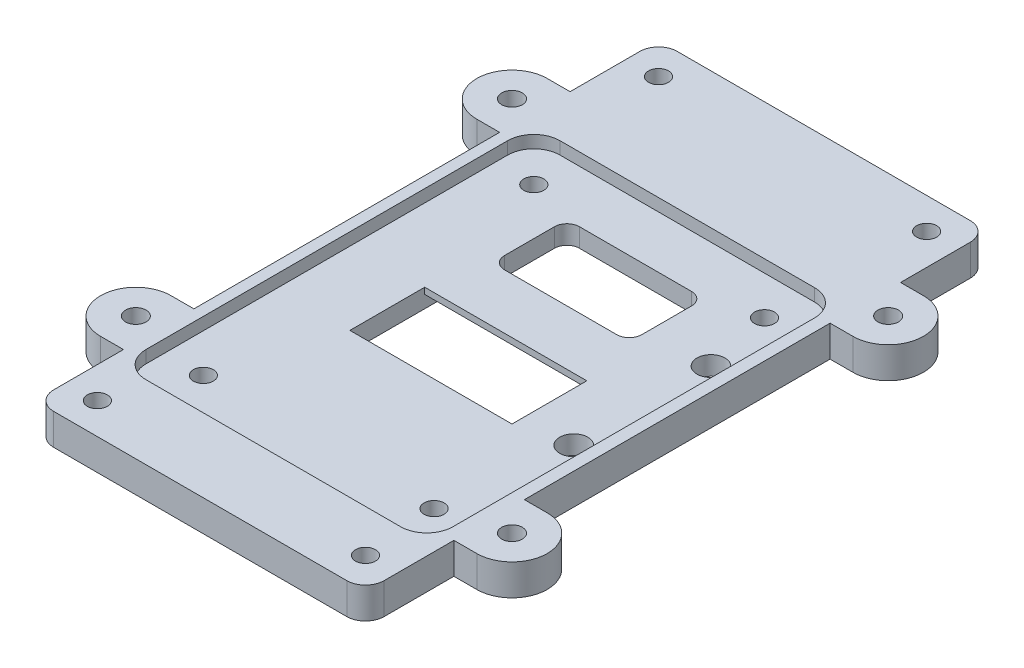
SolidWorks part; units mm, degrees
ref_plane "Front Plane" through (0, 0, 0) normal (0, 0, 1) x (1, 0, 0)
ref_plane "Top Plane" through (0, 0, 0) normal (0, 1, 0) x (1, 0, 0)
ref_plane "Right Plane" through (0, 0, 0) normal (1, 0, 0) x (0, 0, -1)
sketch "Sketch1" plane through (0, 0, 0) normal (0, 1, 0) x (1, 0, 0)
  line L1 (23.5, -32) -> (-23.5, -32)
  line L2 (23.5, -32) -> (23.5, 32)
  line L3 (23.5, 32) -> (-23.5, 32)
  line L4 (-23.5, -32) -> (-23.5, 32)
  line L5 (23.5, -32) -> (-23.5, 32) construction
  line L6 (23.5, 32) -> (-23.5, -32) construction
  point P0 (0, 0)
  dimension "D1" = 47
  dimension "D2" = 64
extrude "Boss-Extrude1" add sketch "Sketch1" along normal blind 5 contours L2 L1 L4 L3
sketch "Sketch2" plane through (0, 5, 0) normal (0, 1, 0) x (1, 0, 0)
  line L0 (-23.5, 0) -> (23.5, 0) construction
  line L1 (-23.5, -32) -> (-23.5, 32) construction
  line L2 (23.5, -32) -> (23.5, 32) construction
  line L3 (0, 0) -> (0, -8) construction
  line L4 (0, -8) -> (13, -8) construction
  line L5 (13, -8) -> (13, 4)
  line L6 (13, 4) -> (-13, 4)
  line L7 (0, 0) -> (0, 18.81) construction
  line L8 (13, -8) -> (-13, -8)
  line L9 (13, -8) -> (13, 4)
  line L10 (13, 4) -> (-13, 4)
  line L11 (-13, -8) -> (-13, 4)
  line L13 (-11, 12.81) -> (11, 12.81)
  line L14 (-11, 12.81) -> (-11, 24.81)
  line L15 (-11, 24.81) -> (11, 24.81)
  line L16 (11, 12.81) -> (11, 24.81)
  line L17 (-11, 12.81) -> (11, 24.81) construction
  line L18 (-11, 24.81) -> (11, 12.81) construction
  dimension "D1" = 8
  dimension "D2" = 13
  dimension "D3" = 12
  dimension "D4" = 26
  dimension "D5" = 18.81
  dimension "D6" = 22
  dimension "D7" = 12
extrude "Cut-Extrude1" cut sketch "Sketch2" against normal blind 5 contours L13 L16 L15 L14 | L11 L8 L5 L6
sketch "Sketch3" plane through (0, 5, 0) normal (0, 1, 0) x (1, 0, 0)
  line L0 (23.5, 32) -> (-23.5, 32) construction
  line L1 (-23.5, -32) -> (-23.5, 32) construction
  line L2 (0, 0) -> (0, 8.2932) construction
  line L3 (23.5, -32) -> (-23.5, -32) construction
  circle A0 centre (-18.5, 27) radius 1.6
  circle A1 centre (18.5, 27) radius 1.6
  circle A2 centre (-18.5, -26) radius 1.6
  circle A3 centre (18.5, -26) radius 1.6
  dimension "D1" = 3.2
  dimension "D4" = 3.2
  dimension "D2" = 5
  dimension "D3" = 5
  dimension "D5" = 5
  dimension "D6" = 6
extrude "Cut-Extrude2" cut sketch "Sketch3" against normal blind 63
fillet "Fillet1" radius 2 4 edges at (11, 2.5, -12.81) (-11, 2.5, -12.81) (11, 2.5, -24.81) (-11, 2.5, -24.81)
fillet "Fillet2" radius 3 4 edges at (23.5, 2.5, -32) (-23.5, 2.5, -32) (23.5, 2.5, 32) (-23.5, 2.5, 32)
sketch "Sketch5" plane through (0, 5, 0) normal (0, 1, 0) x (1, 0, 0)
  line L0 (-23.5, -29) -> (-23.5, 29) construction
  line L1 (-23.5, -25.165) -> (-23.5, 29)
  line L2 (-23.5, 29) -> (-23.5, 5)
  line L3 (-23.5, 5) -> (23.5, 5) construction
  line L4 (23.5, -29) -> (23.5, 29) construction
  line L5 (-30.165, 40.815) -> (-26.5, 40.815)
  line L6 (-30.165, -25.165) -> (-28.515, -25.165)
  line L7 (-30.165, -25.165) -> (-30.165, 35.165)
  line L8 (-30.165, 35.165) -> (15.9874, 35.165)
  line L10 (-30.165, -25.165) -> (-28.9983, -23.9983) construction
  line L11 (-30.165, 35.165) -> (-28.9983, 33.9983) construction
  line L12 (-26.5, -45) -> (26.5, -45)
  line L13 (-26.5, -45) -> (-26.5, -30.815)
  line L14 (-26.5, 55) -> (26.5, 55)
  line L15 (26.5, -45) -> (26.5, -30.815)
  line L16 (-26.5, -45) -> (26.5, 55) construction
  line L17 (-26.5, 55) -> (26.5, -45) construction
  line L18 (-30.165, 29.515) -> (-26.5, 29.515)
  line L19 (-26.5, 40.815) -> (-26.5, 55)
  line L20 (-23.5, 28.5) -> (0, 5) construction
  line L21 (30.165, 40.815) -> (26.5, 40.815)
  line L22 (30.165, 29.515) -> (26.5, 29.515)
  line L23 (28.515, 35.165) -> (30.165, 35.165)
  line L24 (26.5, 40.815) -> (26.5, 55)
  line L25 (26.1698, 31.1698) -> (30.165, 35.165) construction
  line L26 (30.165, 33.515) -> (30.165, 35.165)
  line L27 (-30.165, -19.515) -> (-26.5, -19.515)
  line L28 (-30.165, -30.815) -> (-26.5, -30.815)
  line L29 (-26.5, -19.515) -> (-26.5, 29.515)
  line L30 (-23.5, -18.5) -> (0, 5) construction
  line L31 (-23.5, -25.165) -> (24.515, -25.165)
  line L34 (26.5, -9.515) -> (26.5, 29.515)
  line L35 (28.515, -25.165) -> (30.165, -25.165)
  line L36 (30.165, 35.165) -> (30.165, -25.165)
  line L37 (26.5, -9.515) -> (26.5, -19.515)
  line L38 (0, 0) -> (0, -5.5658) construction
  line L39 (30.165, -19.515) -> (26.5, -19.515)
  line L40 (30.165, -30.815) -> (26.5, -30.815)
  circle A0 centre (-30.165, 35.165) radius 1.65
  circle A1 centre (30.165, 35.165) radius 1.65
  circle A2 centre (30.165, -25.165) radius 1.65
  circle A3 centre (-30.165, -25.165) radius 1.65
  arc A4 (30.165, -19.515) -> (30.165, -30.815) centre (30.165, -25.165) cw
  arc A5 (-30.165, 40.815) -> (-30.165, 29.515) centre (-30.165, 35.165) ccw
  arc A6 (-30.165, -19.515) -> (-30.165, -30.815) centre (-30.165, -25.165) ccw
  arc A8 (30.165, 29.515) -> (30.165, 40.815) centre (30.165, 35.165) ccw
  circle A9 centre (-30.165, 35.165) radius 5.65 construction
  circle A10 centre (30.165, 35.165) radius 5.65 construction
  circle A11 centre (-30.165, -25.165) radius 5.65 construction
  point P2 (0, 5)
  point P15 (0, 5)
  dimension "D4" = 3.3
  dimension "D5" = 3.3
  dimension "D6" = 3.3
  dimension "D7" = 3.3
  dimension "D10" = 4
  dimension "D1" = 24
  dimension "D2" = 60.33
  dimension "D3" = 60.33
  dimension "D8" = 100
  dimension "D9" = 53
extrude "Boss-Extrude3" add sketch "Sketch5" against normal up to surface (5 mm away)
sketch "Sketch6" plane through (0, 5, 0) normal (0, 1, 0) x (1, 0, 0)
  line L0 (23.3314, 0) -> (-23.3314, 0)
  line L1 (0, 0) -> (0, -32) construction
  line L2 (0, 0) -> (0, 32) construction
  line L4 (-23.5, 32) -> (23.5, 32) construction
  line L13 (-20.5, 32) -> (20.3314, 32)
  line L14 (-23.5, 29) -> (-23.5, -29)
  line L15 (-20.5, -32) -> (20.3314, -32)
  line L16 (23.3314, 29) -> (23.3314, -29)
  line L17 (-24.7, 29) -> (-24.7, -29)
  line L18 (-20.5, -33.2) -> (20.3314, -33.2)
  line L19 (24.5314, 29) -> (24.5314, -29)
  line L20 (-20.5, 33.2) -> (20.3314, 33.2)
  arc A0 (20.3314, -32) -> (23.3314, -29) centre (20.3314, -29) ccw
  arc A1 (-20.5, -32) -> (-23.5, -29) centre (-20.5, -29) cw
  arc A2 (23.3314, 29) -> (20.3314, 32) centre (20.3314, 29) ccw
  arc A3 (-20.5, 32) -> (-23.5, 29) centre (-20.5, 29) ccw
  arc A4 (-20.5, -33.2) -> (-24.7, -29) centre (-20.5, -29) cw
  arc A5 (20.3314, -33.2) -> (24.5314, -29) centre (20.3314, -29) ccw
  arc A6 (24.5314, 29) -> (20.3314, 33.2) centre (20.3314, 29) ccw
  arc A7 (-20.5, 33.2) -> (-24.7, 29) centre (-20.5, 29) ccw
  point P4 (0, 0)
  point P10 (0, 32)
  point P11 (0, 32)
  dimension "D1" = 3
  dimension "D3" = 47
extrude "Cut-Extrude5" cut sketch "Sketch6" against normal blind 2
sketch "Sketch7" plane through (0, 0, 0) normal (0, -1, 0) x (1, 0, 0)
  line L0 (-26.5, 45) -> (26.5, 45) construction
  line L1 (-26.5, 45) -> (-26.5, 30.815) construction
  line L2 (0, 0) -> (0, 8) construction
  line L3 (13, 8) -> (-13, 8) construction
  line L4 (-26.5, -40.815) -> (-26.5, -55) construction
  line L5 (-26.5, -55) -> (26.5, -55) construction
  circle A0 centre (-21.5, 40) radius 1.6
  circle A1 centre (21.5, 40) radius 1.6
  circle A2 centre (-21.5, -50) radius 1.6
  circle A3 centre (21.5, -50) radius 1.6
  dimension "D5" = 3.2
  dimension "D6" = 3.2
  dimension "D1" = 5
  dimension "D2" = 5
  dimension "D3" = 5
  dimension "D4" = 5
extrude "Cut-Extrude7" cut sketch "Sketch7" against normal through all
chamfer "Chamfer4" distance 2 angle 45 2 edges at (0, 0, 8) (0, 0, -4)
fillet "Fillet3" radius 3 4 edges at (26.5, 2.5, 45) (-26.5, 2.5, 45) (-26.5, 2.5, -55) (26.5, 2.5, -55)
sketch "Sketch8" plane through (0, 0, 0) normal (0, -1, 0) x (1, 0, 0)
  line L0 (-30.165, -5) -> (30.165, -5) construction
  line L1 (-30.165, -35.165) -> (30.165, -35.165)
  line L2 (-30.165, -35.165) -> (-30.165, 25.165)
  line L3 (-30.165, 25.165) -> (30.165, 25.165)
  line L4 (30.165, -35.165) -> (30.165, 25.165)
  line L5 (20.9063, -16) -> (20.9063, 6)
  line L16 (26.5, 30.815) -> (26.5, 42)
  line L17 (23.5, 45) -> (-23.5, 45)
  line L18 (-26.5, 42) -> (-26.5, 30.815)
  line L19 (-26.5, 30.815) -> (-30.165, 30.815)
  line L20 (-30.165, 19.515) -> (-26.5, 19.515)
  line L21 (-26.5, 19.515) -> (-26.5, -29.515)
  line L22 (-26.5, -29.515) -> (-30.165, -29.515)
  line L23 (-30.165, -40.815) -> (-26.5, -40.815)
  line L24 (-26.5, -40.815) -> (-26.5, -52)
  line L25 (-23.5, -55) -> (23.5, -55)
  line L26 (26.5, -52) -> (26.5, -40.815)
  line L27 (26.5, -40.815) -> (30.165, -40.815)
  line L28 (30.165, -29.515) -> (26.5, -29.515)
  line L29 (26.5, -29.515) -> (26.5, 19.515)
  line L30 (26.5, 19.515) -> (30.165, 19.515)
  line L31 (30.165, 30.815) -> (26.5, 30.815)
  line L32 (26.5, 30.815) -> (26.5, 42)
  line L33 (23.5, 45) -> (-23.5, 45)
  line L34 (-26.5, 42) -> (-26.5, 30.815)
  line L35 (-26.5, 30.815) -> (-30.165, 30.815)
  line L36 (-30.165, 19.515) -> (-26.5, 19.515)
  line L37 (-26.5, 19.515) -> (-26.5, -29.515)
  line L38 (-26.5, -29.515) -> (-30.165, -29.515)
  line L39 (-30.165, -40.815) -> (-26.5, -40.815)
  line L40 (-26.5, -40.815) -> (-26.5, -52)
  line L41 (-23.5, -55) -> (23.5, -55)
  line L42 (26.5, -52) -> (26.5, -40.815)
  line L43 (26.5, -40.815) -> (30.165, -40.815)
  line L44 (30.165, -29.515) -> (26.5, -29.515)
  line L45 (26.5, -29.515) -> (26.5, 19.515)
  line L46 (26.5, 19.515) -> (30.165, 19.515)
  line L47 (30.165, 30.815) -> (26.5, 30.815)
  circle A0 centre (20.9063, -16) radius 2.25
  circle A1 centre (20.9063, 6) radius 2.25
  arc A8 (26.5, 42) -> (23.5, 45) centre (23.5, 42) ccw
  arc A9 (-23.5, 45) -> (-26.5, 42) centre (-23.5, 42) ccw
  arc A10 (-30.165, 30.815) -> (-30.165, 19.515) centre (-30.165, 25.165) ccw
  arc A11 (-30.165, -29.515) -> (-30.165, -40.815) centre (-30.165, -35.165) ccw
  arc A12 (-26.5, -52) -> (-23.5, -55) centre (-23.5, -52) ccw
  arc A13 (23.5, -55) -> (26.5, -52) centre (23.5, -52) ccw
  arc A14 (30.165, -40.815) -> (30.165, -29.515) centre (30.165, -35.165) ccw
  arc A15 (30.165, 19.515) -> (30.165, 30.815) centre (30.165, 25.165) ccw
  arc A16 (26.5, 42) -> (23.5, 45) centre (23.5, 42) ccw
  arc A17 (-23.5, 45) -> (-26.5, 42) centre (-23.5, 42) ccw
  arc A18 (-30.165, 30.815) -> (-30.165, 19.515) centre (-30.165, 25.165) ccw
  arc A19 (-30.165, -29.515) -> (-30.165, -40.815) centre (-30.165, -35.165) ccw
  arc A20 (-26.5, -52) -> (-23.5, -55) centre (-23.5, -52) ccw
  arc A21 (23.5, -55) -> (26.5, -52) centre (23.5, -52) ccw
  arc A22 (30.165, -40.815) -> (30.165, -29.515) centre (30.165, -35.165) ccw
  arc A23 (30.165, 19.515) -> (30.165, 30.815) centre (30.165, 25.165) ccw
  point P24 (20.9063, -5)
  dimension "D2" = 4.5
  dimension "D3" = 22
  dimension "D1" = 0
extrude "Cut-Extrude8" cut sketch "Sketch8" against normal through all
sketch "Sketch9" plane through (0, 5, 0) normal (0, 1, 0) x (1, 0, 0)
  line L16 (-23.5, -45) -> (23.5, -45)
  line L17 (26.5, -42) -> (26.5, -30.815)
  line L18 (26.5, -30.815) -> (30.165, -30.815)
  line L19 (30.165, -19.515) -> (26.5, -19.515)
  line L20 (26.5, -19.515) -> (26.5, 29.515)
  line L21 (26.5, 29.515) -> (30.165, 29.515)
  line L22 (30.165, 40.815) -> (26.5, 40.815)
  line L23 (26.5, 40.815) -> (26.5, 52)
  line L24 (23.5, 55) -> (-23.5, 55)
  line L25 (-26.5, 52) -> (-26.5, 40.815)
  line L26 (-26.5, 40.815) -> (-30.165, 40.815)
  line L27 (-30.165, 29.515) -> (-26.5, 29.515)
  line L28 (-26.5, 29.515) -> (-26.5, -19.515)
  line L29 (-26.5, -19.515) -> (-30.165, -19.515)
  line L30 (-30.165, -30.815) -> (-26.5, -30.815)
  line L31 (-26.5, -30.815) -> (-26.5, -42)
  line L32 (-23.5, -45) -> (23.5, -45)
  line L33 (26.5, -42) -> (26.5, -30.815)
  line L34 (26.5, -30.815) -> (30.165, -30.815)
  line L35 (30.165, -19.515) -> (26.5, -19.515)
  line L36 (26.5, -19.515) -> (26.5, 29.515)
  line L37 (26.5, 29.515) -> (30.165, 29.515)
  line L38 (30.165, 40.815) -> (26.5, 40.815)
  line L39 (26.5, 40.815) -> (26.5, 52)
  line L40 (23.5, 55) -> (-23.5, 55)
  line L41 (-26.5, 52) -> (-26.5, 40.815)
  line L42 (-26.5, 40.815) -> (-30.165, 40.815)
  line L43 (-30.165, 29.515) -> (-26.5, 29.515)
  line L44 (-26.5, 29.515) -> (-26.5, -19.515)
  line L45 (-26.5, -19.515) -> (-30.165, -19.515)
  line L46 (-30.165, -30.815) -> (-26.5, -30.815)
  line L47 (-26.5, -30.815) -> (-26.5, -42)
  circle A0 centre (-21.5, 50) radius 1.6 construction
  circle A1 centre (-21.5, 50) radius 1.6
  circle A2 centre (21.5, 50) radius 1.6 construction
  circle A3 centre (21.5, 50) radius 1.6
  circle A4 centre (-21.5, -40) radius 1.6 construction
  circle A5 centre (-21.5, -40) radius 1.6
  circle A6 centre (21.5, -40) radius 1.6 construction
  circle A7 centre (21.5, -40) radius 1.6
  arc A8 (23.5, -45) -> (26.5, -42) centre (23.5, -42) ccw
  arc A9 (30.165, -30.815) -> (30.165, -19.515) centre (30.165, -25.165) ccw
  arc A10 (30.165, 29.515) -> (30.165, 40.815) centre (30.165, 35.165) ccw
  arc A11 (26.5, 52) -> (23.5, 55) centre (23.5, 52) ccw
  arc A12 (-23.5, 55) -> (-26.5, 52) centre (-23.5, 52) ccw
  arc A13 (-30.165, 40.815) -> (-30.165, 29.515) centre (-30.165, 35.165) ccw
  arc A14 (-30.165, -19.515) -> (-30.165, -30.815) centre (-30.165, -25.165) ccw
  arc A15 (-26.5, -42) -> (-23.5, -45) centre (-23.5, -42) ccw
  arc A16 (23.5, -45) -> (26.5, -42) centre (23.5, -42) ccw
  arc A17 (30.165, -30.815) -> (30.165, -19.515) centre (30.165, -25.165) ccw
  arc A18 (30.165, 29.515) -> (30.165, 40.815) centre (30.165, 35.165) ccw
  arc A19 (26.5, 52) -> (23.5, 55) centre (23.5, 52) ccw
  arc A20 (-23.5, 55) -> (-26.5, 52) centre (-23.5, 52) ccw
  arc A21 (-30.165, 40.815) -> (-30.165, 29.515) centre (-30.165, 35.165) ccw
  arc A22 (-30.165, -19.515) -> (-30.165, -30.815) centre (-30.165, -25.165) ccw
  arc A23 (-26.5, -42) -> (-23.5, -45) centre (-23.5, -42) ccw
  dimension "D2" = 43
  dimension "D3" = 90
  dimension "D1" = 0
